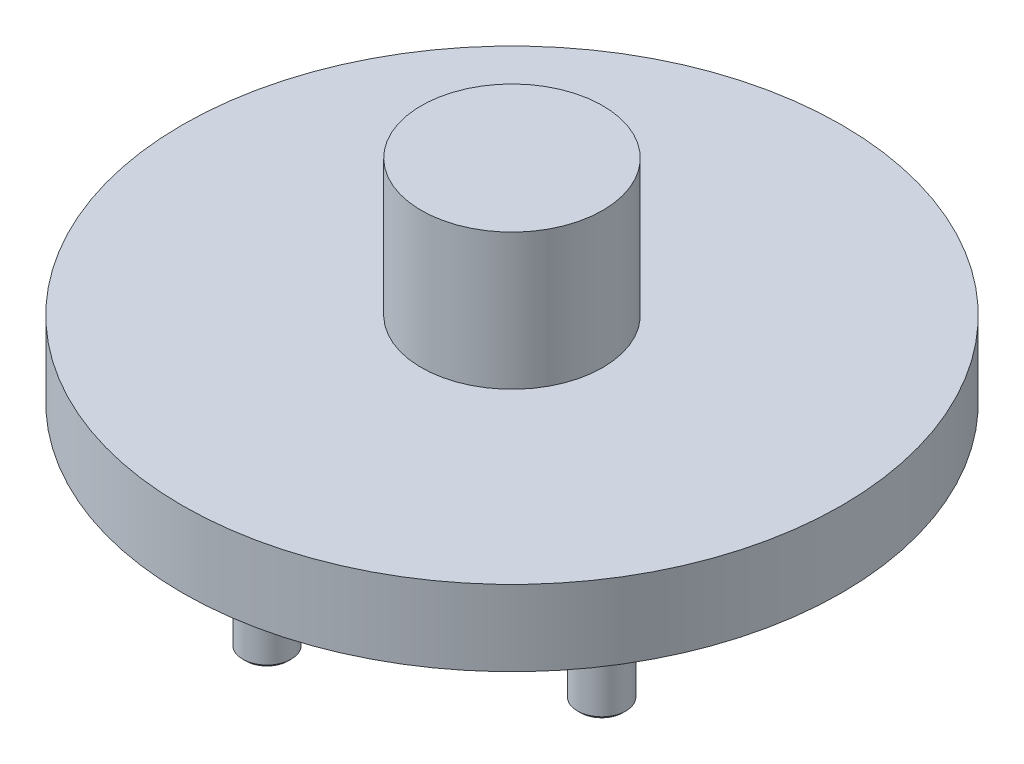
SolidWorks part; units mm, degrees
ref_plane "Front Plane" through (0, 0, 0) normal (0, 0, 1) x (1, 0, 0)
ref_plane "Top Plane" through (0, 0, 0) normal (0, 1, 0) x (1, 0, 0)
ref_plane "Right Plane" through (0, 0, 0) normal (1, 0, 0) x (0, 0, -1)
sketch "Sketch1" plane through (0, 0, 0) normal (0, 0, 1) x (1, 0, 0)
  line L0 (0, 0) -> (53, 0)
  line L1 (53, 0) -> (53, 5)
  line L2 (53, 5) -> (109, 5)
  line L3 (109, 5) -> (109, 30)
  line L4 (109, 30) -> (30, 30)
  line L5 (30, 30) -> (30, 75)
  line L6 (30, 75) -> (0, 75)
  line L7 (0, 75) -> (0, 0)
  line L8 (0, 0) -> (0, 110.0074) construction
  dimension "D1" = 53
  dimension "D2" = 75
  dimension "D3" = 30
  dimension "D4" = 45
  dimension "D5" = 25
  dimension "D6" = 56
revolve "Revolve1" add sketch "Sketch1" angle 360 about L8
sketch "Sketch2" plane through (0, 5, 0) normal (0, -1, 0) x (1, 0, 0)
  circle A0 centre (0, 81) radius 8
  dimension "D1" = 16
  dimension "D2" = 81
extrude "Boss-Extrude1" add sketch "Sketch2" along normal blind 30
chamfer "Chamfer1" distance 1 angle 45 1 edges at (8, -25, 81)
pattern_circular "CirPattern3" count 6 every 60 about axis through (0, 0, 0) along (0, 1, 0) of "Chamfer1", "Boss-Extrude1"
